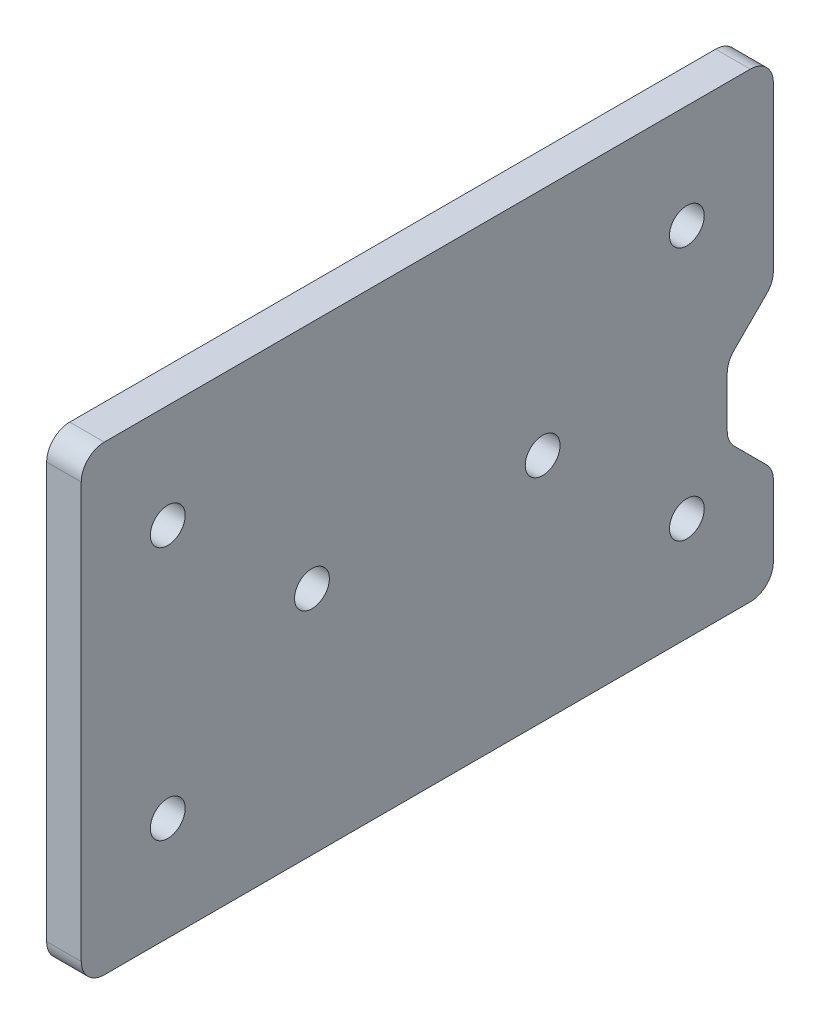
SolidWorks part; units mm, degrees
material "Thornel Mat VMA"
ref_plane "前视基准面" through (0, 0, 0) normal (0, 0, 1) x (1, 0, 0)
ref_plane "上视基准面" through (0, 0, 0) normal (0, 1, 0) x (1, 0, 0)
ref_plane "右视基准面" through (0, 0, 0) normal (1, 0, 0) x (0, 0, -1)
other "Configuration Table"
sketch "草图1" plane through (0, 0, 0) normal (1, 0, 0) x (0, 0, -1)
  line L1 (-30, 20) -> (30, 20)
  line L2 (-30, 20) -> (-30, -20)
  line L3 (-30, -20) -> (30, -20)
  line L4 (30, 20) -> (30, -20)
  line L5 (-30, 20) -> (30, -20) construction
  line L6 (-30, -20) -> (30, 20) construction
  point P0 (0, 0)
  dimension "D1" = 60
  dimension "D2" = 40
extrude "凸台-拉伸1" add sketch "草图1" along normal blind 3
sketch "草图2" plane through (0, 0, 0) normal (-1, 0, 0) x (0, 0, 1)
  line L1 (22.5, 11) -> (-22.5, 11) construction
  line L2 (22.5, 11) -> (22.5, -11) construction
  line L3 (22.5, -11) -> (-22.5, -11) construction
  line L4 (-22.5, 11) -> (-22.5, -11) construction
  line L5 (22.5, 11) -> (-22.5, -11) construction
  line L6 (22.5, -11) -> (-22.5, 11) construction
  circle A0 centre (-22.5, -11) radius 1.51
  circle A1 centre (22.5, -11) radius 1.51
  circle A2 centre (22.5, 11) radius 1.51
  circle A3 centre (-22.5, 11) radius 1.51
  dimension "D3" = 3.02
  dimension "D1" = 22
  dimension "D2" = 45
extrude "切除-拉伸1" cut sketch "草图2" against normal blind 10
sketch "草图3" plane through (0, 0, 0) normal (-1, 0, 0) x (0, 0, 1)
  line L0 (30, 0) -> (-30, 0) construction
  line L1 (30, -20) -> (-30, -20) construction
  line L2 (-30, -20) -> (-30, 20) construction
  line L3 (30, 20) -> (30, -20) construction
  circle A0 centre (10, 0) radius 1.51
  circle A1 centre (-10, 0) radius 1.51
  dimension "D3" = 3.02
  dimension "D1" = 20
  dimension "D2" = 20
  dimension "D4" = 20
extrude "切除-拉伸2" cut sketch "草图3" against normal blind 10
sketch "草图4" plane through (3, 0, 0) normal (1, 0, 0) x (0, 0, -1)
  line L0 (30, -11) -> (26, -7)
  line L1 (26, -7) -> (26, -1)
  line L2 (26, -1) -> (30, 3)
  line L4 (30, -20) -> (30, 20)
  line L5 (30, 20) -> (-30, 20)
  line L6 (-30, 20) -> (-30, -20)
  line L7 (-30, -20) -> (30, -20)
  line L8 (30, -20) -> (30, 20)
  line L9 (30, 20) -> (-30, 20)
  line L10 (-30, 20) -> (-30, -20)
  line L11 (-30, -20) -> (30, -20)
  point P8 (26.4991, -1.775)
  point P9 (26.4355, -7.4039)
  line M14 (30, -20) -> (30, 20)
  dimension "D2" = 45
  dimension "D3" = 45
  dimension "D4" = 4
  dimension "D5" = 13
  dimension "D6" = 14
  dimension "D1" = 0
extrude "切除-拉伸3" cut sketch "草图4" against normal blind 10 contours L2 L1 L0 M14
fillet "圆角1" radius 2 8 edges at (1.5, 3, -30) (1.5, 20, -30) (1.5, 20, 30) (1.5, -20, 30) (1.5, -20, -30) (1.5, -11, -30) (1.5, -1, -26) (1.5, -7, -26)
